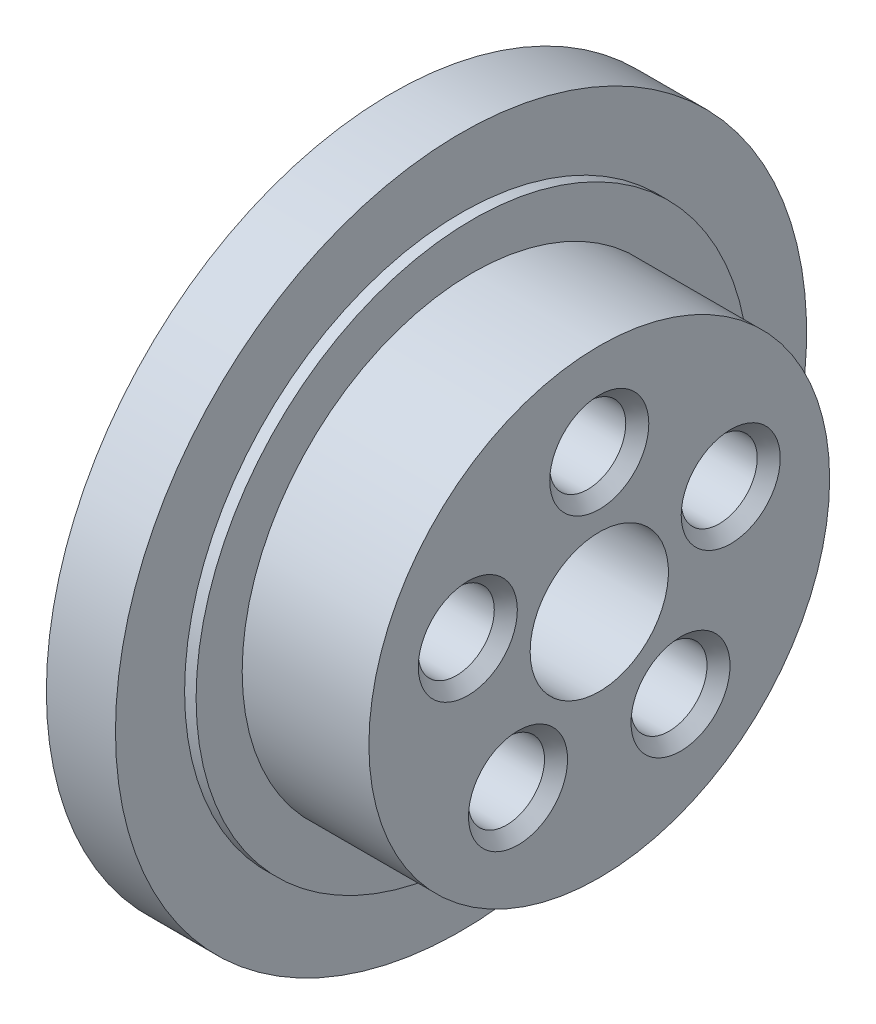
SolidWorks part; units mm, degrees
ref_plane "Front Plane" through (0, 0, 0) normal (0, 0, 1) x (1, 0, 0)
ref_plane "Top Plane" through (0, 0, 0) normal (0, 1, 0) x (1, 0, 0)
ref_plane "Right Plane" through (0, 0, 0) normal (1, 0, 0) x (0, 0, -1)
sketch "Sketch1" plane through (0, 0, 0) normal (0, 0, 1) x (1, 0, 0)
  line L0 (0, 30) -> (6, 30)
  line L9 (6, 30) -> (6, 24)
  line L10 (6, 24) -> (7, 24)
  line L11 (7, 24) -> (7, 20)
  line L12 (7, 20) -> (18, 20)
  line L13 (18, 20) -> (18, 6)
  line L14 (18, 6) -> (6, 6)
  line L15 (6, 6) -> (6, 7.5)
  line L16 (6, 7.5) -> (0, 7.5)
  line L17 (0, 7.5) -> (0, 30)
  line L18 (0, 0) -> (18, 0) construction
  dimension "D1" = 6
  dimension "D2" = 12
  dimension "D3" = 1
  dimension "D4" = 6
  dimension "D5" = 4
  dimension "D6" = 7.5
  dimension "D7" = 30
  dimension "D8" = 14
  dimension "D9" = 6
revolve "Revolve1" add sketch "Sketch1" angle 360 about L18
sketch "Sketch2" plane through (0, 0, 0) normal (-1, 0, 0) x (0, 0, 1)
  circle A0 centre (0, 0) radius 20 construction
  circle A1 centre (0, 20) radius 2.5
  circle A2 centre (17.3205, 10) radius 2.5
  circle A3 centre (17.3205, -10) radius 2.5
  circle A4 centre (0, -20) radius 2.5
  circle A5 centre (-17.3205, -10) radius 2.5
  circle A6 centre (-17.3205, 10) radius 2.5
  point P18 (0, 0)
  dimension "D1" = 40
  dimension "D2" = 5
extrude "Cut-Extrude1" cut sketch "Sketch2" against normal blind 4
sketch "Sketch3" plane through (18, 0, 0) normal (1, 0, 0) x (0, 0, -1)
  circle A0 centre (0, 0) radius 12 construction
  circle A3 centre (0, 12) radius 3.3
  circle A6 centre (11.4127, 3.7082) radius 3.3
  circle A7 centre (7.0534, -9.7082) radius 3.3
  circle A8 centre (-7.0534, -9.7082) radius 3.3
  circle A9 centre (-11.4127, 3.7082) radius 3.3
  point P15 (0, 0)
  dimension "D1" = 24
  dimension "D2" = 6.6
extrude "Cut-Extrude2" cut sketch "Sketch3" against normal blind 10.5
chamfer "Chamfer1" distance 1 angle 45 5 edges at (18, 3.7082, 8.1127) (18, -9.7082, 3.7534) (18, -9.7082, -10.3534) (18, 3.7082, -14.7127) (18, 12, -3.3)
sketch "Sketch4" [suppressed] plane through (6, 0, 0) normal (-1, 0, 0) x (0, 0, 1)
  circle A0 centre (0, 0) radius 6.5
  dimension "D1" = 13
extrude "Cut-Extrude3" [suppressed] cut sketch "Sketch4" against normal through all
equation "\"R_ROLL\"= 5mm"
equation "\"D_SUN\"= 80mm"
equation "\"NUM_ROLL\"= 16"
equation "\"RHO\"= 1mm"
equation "\"D_SHAFT\"= 15mm"
equation "\"D_OUTPUT\"= 40mm"
equation "\"NUM_OUT\"= 6"
equation "\"R_OUT_ROLL\"= 5mm"
equation "\"D1@Sketch2\"=\"D_OUTPUT\""
